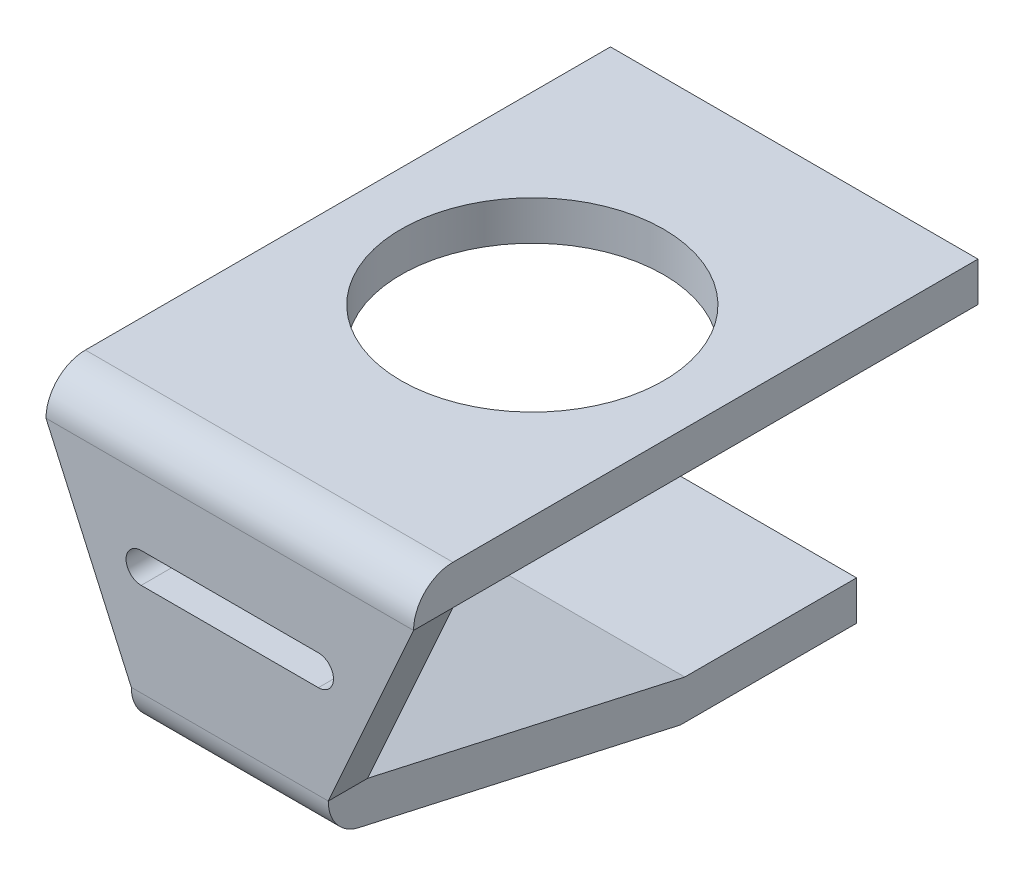
SolidWorks part; units mm, degrees
ref_plane "Спереди" through (0, 0, 0) normal (0, 0, 1) x (1, 0, 0)
ref_plane "Сверху" through (0, 0, 0) normal (0, 1, 0) x (1, 0, 0)
ref_plane "Справа" through (0, 0, 0) normal (1, 0, 0) x (0, 0, -1)
sketch "Эскиз1" plane through (0, 0, 0) normal (1, 0, 0) x (0, 0, -1)
  line L0 (0, 15.8128) -> (0, -19.6478) construction
  line L1 (-12.7613, 0) -> (2, 0) construction
  line L2 (-2, -0.15) -> (2, -0.15)
  line L3 (-2.3, 0.15) -> (2, 0.15)
  line L4 (2, 0.15) -> (2, -0.15)
  line L5 (-2, -0.15) -> (-2, -1.6004)
  line L6 (0, -0.15) -> (43.9039, -0.15) construction
  line L7 (0, 0) -> (43.9039, 0) construction
  line L8 (0, 0.15) -> (43.9039, 0.15) construction
  line L9 (-2, -1.6004) -> (0.4163, -2.1403)
  line L10 (0.4163, -2.1403) -> (1.7248, -2.1403)
  line L11 (-2.3, -0.15) -> (-2.3, -1.8407)
  line L12 (-2.3, -1.8407) -> (0.3832, -2.4403)
  line L13 (0.3832, -2.4403) -> (1.7248, -2.4403)
  line L14 (1.7248, -2.4403) -> (1.7248, -2.1403)
  line L15 (-2.3, 0.15) -> (-2.3, -0.15)
  dimension "D4" = 4
  dimension "D1" = 0.15
  dimension "D2" = 0.15
  dimension "D3" = 0.3
extrude "Бобышка-Вытянуть1" add sketch "Эскиз1" against normal blind 2.8
sketch "Эскиз2" plane through (0, 0.15, 0) normal (0, 1, 0) x (1, 0, 0)
  line L0 (-2.8, 2) -> (0, 2) construction
  line L1 (0, 2) -> (0, -2.3) construction
  circle A0 centre (-1.395, 0) radius 1
  dimension "D1" = 2
  dimension "D2" = 2
  dimension "D3" = 1.395
extrude "Вырез-Вытянуть1" cut sketch "Эскиз2" against normal blind 0.35
sketch "Эскиз3" plane through (0, 0, 2.3) normal (0, 0, 1) x (1, 0, 0)
  line L0 (0, -0.15) -> (-0.65, -1.6008)
  line L1 (-2.8, -1.8407) -> (0, -1.8407) construction
  line L2 (-2.15, -1.8407) -> (-0.5075, -1.8407)
  line L3 (-0.65, -1.8407) -> (-0.65, -1.6008)
  line L4 (-2.9429, -0.15) -> (-2.8, -0.15)
  line L5 (-2.9429, -0.15) -> (-2.9429, -2.9797)
  line L6 (-2.9429, -2.9797) -> (0.1046, -2.9797)
  line L7 (0.1046, -2.9797) -> (0.1046, -0.15)
  line L8 (0.1046, -0.15) -> (0, -0.15)
  line L9 (-2.15, -1.8407) -> (-2.15, -2.5822)
  line L10 (-0.65, -1.8407) -> (-0.65, -2.5822)
  line L11 (-2.15, -2.5822) -> (-0.65, -2.5822)
  line L12 (-2.8, -0.15) -> (-2.15, -1.6008)
  line L13 (-2.15, -1.8407) -> (-2.15, -1.6008)
  line L14 (-2.15, -1.6008) -> (-0.65, -1.6008) construction
  line L15 (-2.8, 0.15) -> (-2.8, -1.8407) construction
  line L16 (-2.8, 0.15) -> (0, 0.15) construction
  line L17 (-1.4, 0.15) -> (-1.4, -1.6008) construction
  dimension "D1" = 0.2399
  dimension "D2" = 3.0475
  dimension "D3" = 1.5
extrude "Вырез-Вытянуть2" cut sketch "Эскиз3" against normal blind 5.84
fillet "Скругление1" radius 0.3 1 edges at (-1.4, 0.15, 2.3)
fillet "Скругление2" radius 0.3 1 edges at (-1.4, -1.8407, 2.3)
sketch "Эскиз4" plane through (0, 0, 2.3) normal (0, 0, 1) x (1, 0, 0)
  line L0 (-1.4, -1.6004) -> (-1.4, -0.15) construction
  line L1 (-2.1502, -1.6004) -> (-0.6498, -1.6004) construction
  line L2 (0, -0.15) -> (-2.8, -0.15) construction
  line L3 (-2.075, -0.775) -> (-0.725, -0.775) construction
  line L4 (-2.075, -0.775) -> (-0.725, -0.775) construction
  line L5 (-2.075, -0.6599) -> (-0.725, -0.6599)
  line L6 (-2.075, -0.8901) -> (-0.725, -0.8901)
  arc A0 (-2.075, -0.6599) -> (-2.075, -0.8901) centre (-2.075, -0.775) ccw
  arc A1 (-0.725, -0.8901) -> (-0.725, -0.6599) centre (-0.725, -0.775) ccw
  point P11 (-1.4, -0.775)
extrude "Вырез-Вытянуть3" cut sketch "Эскиз4" against normal blind 0.38
